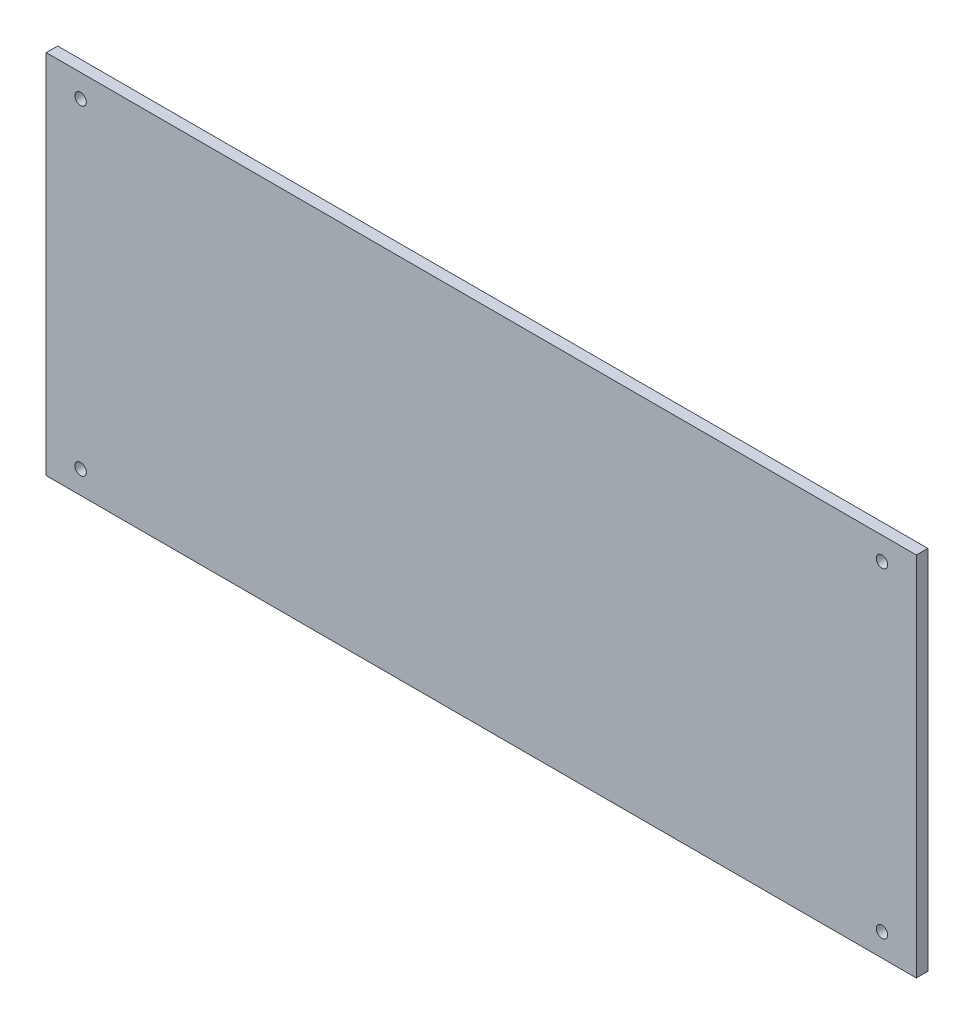
SolidWorks part; units mm, degrees
ref_plane "Front Plane" through (0, 0, 0) normal (0, 0, 1) x (1, 0, 0)
ref_plane "Top Plane" through (0, 0, 0) normal (0, 1, 0) x (1, 0, 0)
ref_plane "Right Plane" through (0, 0, 0) normal (1, 0, 0) x (0, 0, -1)
sketch "Sketch1" plane through (0, 0, 0) normal (0, 0, 1) x (1, 0, 0)
  line L1 (-241.3, -101.6) -> (241.3, -101.6)
  line L2 (-241.3, -101.6) -> (-241.3, 101.6)
  line L3 (-241.3, 101.6) -> (241.3, 101.6)
  line L4 (241.3, -101.6) -> (241.3, 101.6)
  line L5 (-241.3, -101.6) -> (241.3, 101.6) construction
  line L6 (-241.3, 101.6) -> (241.3, -101.6) construction
  point P0 (0, 0)
  dimension "D1" = 482.6
  dimension "D2" = 203.2
extrude "Boss-Extrude1" add sketch "Sketch1" along normal blind 6.35
sketch "Sketch2" plane through (0, 0, 6.35) normal (0, 0, 1) x (1, 0, 0)
  line L0 (-241.3, 101.6) -> (-241.3, -101.6) construction
  line L1 (-241.3, -101.6) -> (241.3, -101.6) construction
  circle A0 centre (-222.25, -88.9) radius 3.175
  dimension "D3" = 6.35
  dimension "D1" = 19.05
  dimension "D2" = 12.7
extrude "Cut-Extrude1" cut sketch "Sketch2" against normal through all
mirror "Mirror1" about plane through (0, 0, 0) normal (1, 0, 0) of "Cut-Extrude1" second plane through (0, 0, 0) second plane normal (0, 1, 0)
